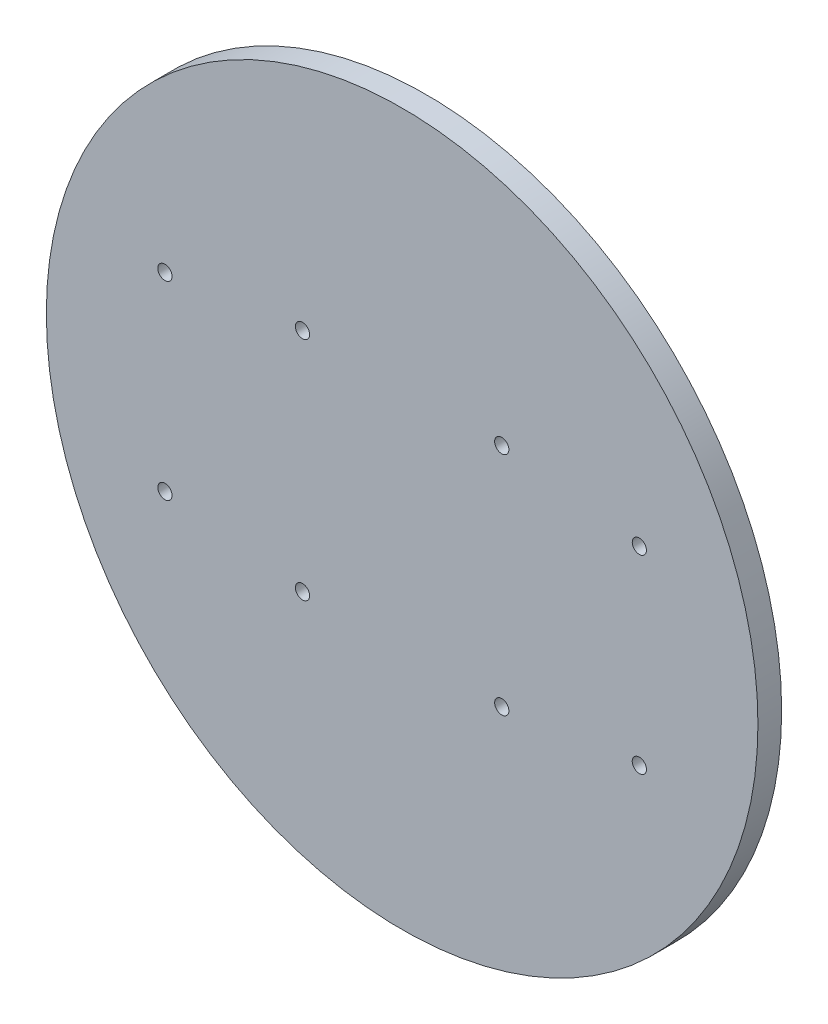
SolidWorks part; units mm, degrees
material "PMMA"
ref_plane "Alzado" through (0, 0, 0) normal (0, 0, 1) x (1, 0, 0)
ref_plane "Planta" through (0, 0, 0) normal (0, 1, 0) x (1, 0, 0)
ref_plane "Vista lateral" through (0, 0, 0) normal (1, 0, 0) x (0, 0, -1)
sketch "Croquis1" plane through (0, 0, 0) normal (0, 0, 1) x (1, 0, 0)
  circle A0 centre (0, 0) radius 75
  dimension "D1" = 150
extrude "Saliente-Extruir1" add sketch "Croquis1" along normal blind 5
sketch "Croquis2" plane through (0, 0, 5) normal (0, 0, 1) x (1, 0, 0)
  line L0 (-75, 0) -> (75, 0) construction
  line L1 (-50, 20) -> (-50, 0) construction
  line L2 (0, 75) -> (0, -75) construction
  circle A0 centre (0, 0) radius 75 construction
  circle A1 centre (-50, 20) radius 1.5
  circle A2 centre (-50, -20) radius 1.5
  circle A3 centre (50, -20) radius 1.5
  circle A4 centre (50, 20) radius 1.5
  circle A5 centre (21, 23.876) radius 1.5
  circle A6 centre (-21, 23.876) radius 1.5
  circle A7 centre (-21, -23.8) radius 1.5
  circle A8 centre (21, -23.8) radius 1.5
  dimension "D1" = 20
  dimension "D2" = 25
extrude "Cortar-Extruir1" cut sketch "Croquis2" against normal through all
sketch "Croquis3" [suppressed] plane through (0, 0, 0) normal (0, 0, 1) x (1, 0, 0)
  circle A0 centre (0, 0) radius 75 construction
  circle A1 centre (-50, 20) radius 1.5 construction
  circle A2 centre (-50, -20) radius 1.5 construction
  circle A3 centre (-21, 23.876) radius 1.5 construction
  circle A4 centre (-21, -23.8) radius 1.5 construction
  circle A5 centre (21, 23.876) radius 1.5 construction
  circle A6 centre (21, -23.8) radius 1.5 construction
  circle A7 centre (50, 20) radius 1.5 construction
  circle A8 centre (50, -20) radius 1.5 construction
  circle A9 centre (0, 0) radius 75
  circle A10 centre (-50, 20) radius 1.5
  circle A11 centre (-50, -20) radius 1.5
  circle A12 centre (-21, 23.876) radius 1.5
  circle A13 centre (-21, -23.8) radius 1.5
  circle A14 centre (21, 23.876) radius 1.5
  circle A15 centre (21, -23.8) radius 1.5
  circle A16 centre (50, 20) radius 1.5
  circle A17 centre (50, -20) radius 1.5
